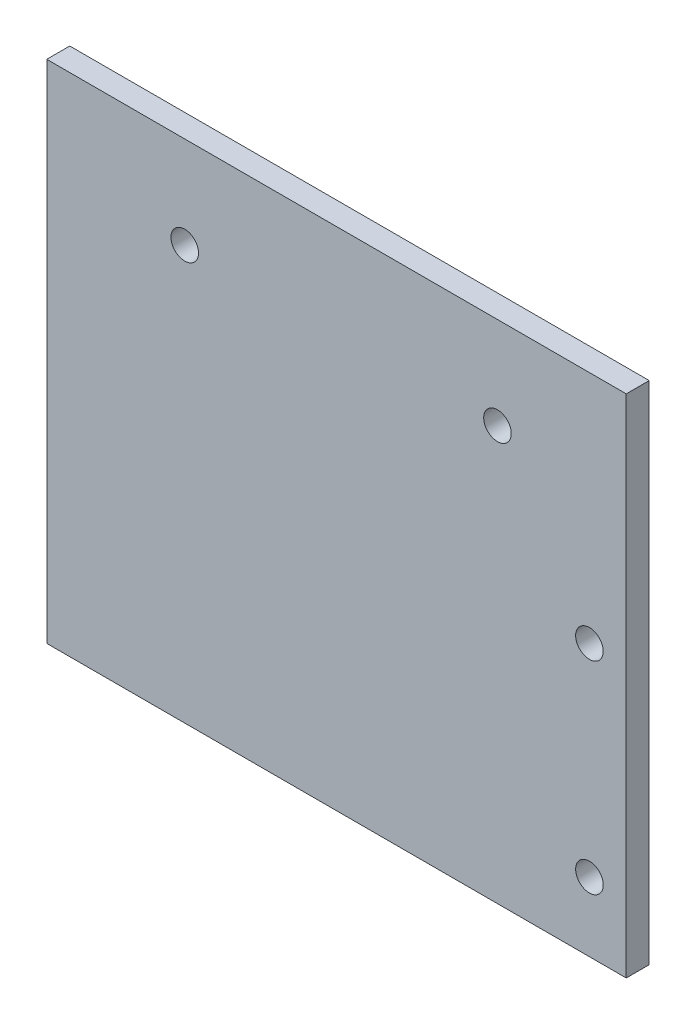
SolidWorks part; units mm, degrees
material "1023 Carbon Steel Sheet (SS)"
ref_plane "Front Plane" through (0, 0, 0) normal (0, 0, 1) x (1, 0, 0)
ref_plane "Top Plane" through (0, 0, 0) normal (0, 1, 0) x (1, 0, 0)
ref_plane "Right Plane" through (0, 0, 0) normal (1, 0, 0) x (0, 0, -1)
sketch "Sketch1" plane through (0, 0, 0) normal (0, 0, 1) x (1, 0, 0)
  line L1 (-81.5, 75) -> (81.5, 75)
  line L2 (-81.5, 75) -> (-81.5, -75)
  line L3 (-81.5, -75) -> (81.5, -75)
  line L4 (81.5, 75) -> (81.5, -75)
  line L5 (-81.5, 75) -> (81.5, -75) construction
  line L6 (-81.5, -75) -> (81.5, 75) construction
  point P0 (0, 0)
  dimension "D1" = 163
  dimension "D2" = 150
extrude "Boss-Extrude1" add sketch "Sketch1" along normal blind 2.5 contours L3 L4 L1 L2
sketch "Sketch3" plane through (0, 0, 2.5) normal (0, 0, 1) x (1, 0, 0)
  line L0 (-81.5, -75) -> (-50.5, -75)
  line L1 (-81.5, 75) -> (-81.5, -75) construction
  line L2 (-81.5, -75) -> (81.5, -75) construction
  line L3 (-50.5, -75) -> (-50.5, -30)
  line L4 (-67.5, -30) -> (-33.5, -30)
  line L5 (-62.5, -56.5) -> (-77.5, -56.5)
  line L6 (-50.5, -30) -> (-62.5, -30)
  line L7 (-50.5, -30) -> (-50.5, -56.5)
  line L8 (-50.5, -56.5) -> (-62.5, -56.5)
  line L9 (-62.5, -30) -> (-62.5, -56.5)
  line L10 (-77.5, -45.5) -> (-77.5, -67.5)
  circle A0 centre (-67.5, -30) radius 1.5
  circle A1 centre (-33.5, -30) radius 1.5
  circle A2 centre (-77.5, -45.5) radius 1.5
  circle A3 centre (-77.5, -67.5) radius 1.5
  point P10 (-50.5, -30)
  point P19 (-77.5, -56.5)
  dimension "D1" = 3
  dimension "D2" = 3
  dimension "D8" = 3
  dimension "D9" = 3
  dimension "D3" = 34
  dimension "D4" = 26.5
  dimension "D5" = 12
  dimension "D6" = 15
  dimension "D7" = 22
  dimension "D10" = 45
  dimension "D11" = 31
extrude "Cut-Extrude1" cut sketch "Sketch3" against normal blind 2.5 contours A1 | A0 | A2 | A3
mirror "Mirror1" about plane through (0, 0, 0) normal (1, 0, 0) of "Cut-Extrude1"
sketch "Sketch4" plane through (0, 0, 2.5) normal (0, 0, 1) x (1, 0, 0)
  line L0 (-81.5, 75) -> (0, 75)
  line L1 (-81.5, 75) -> (81.5, 75) construction
  line L2 (0, 75) -> (0, 10)
  line L3 (0, 10) -> (-32.5, 10)
  line L4 (-32.5, 27.5) -> (-32.5, -7.5)
  line L5 (34.5, -18.5) -> (30.5, -18.5)
  line L6 (-34.5, 38.5) -> (-30.5, 38.5)
  line L7 (-34.5, 38.5) -> (-34.5, 16.5)
  line L8 (-34.5, 16.5) -> (-30.5, 16.5)
  line L9 (-30.5, 38.5) -> (-30.5, 16.5)
  line L10 (-34.5, 38.5) -> (-30.5, 16.5) construction
  line L11 (-34.5, 16.5) -> (-30.5, 38.5) construction
  line L12 (-34.5, 3.5) -> (-30.5, 3.5)
  line L13 (-34.5, 3.5) -> (-34.5, -18.5)
  line L14 (-34.5, -18.5) -> (-30.5, -18.5)
  line L15 (-30.5, 3.5) -> (-30.5, -18.5)
  line L16 (-34.5, 3.5) -> (-30.5, -18.5) construction
  line L17 (-34.5, -18.5) -> (-30.5, 3.5) construction
  line L18 (30.5, 3.5) -> (30.5, -18.5)
  line L19 (34.5, 3.5) -> (30.5, 3.5)
  line L20 (34.5, 3.5) -> (34.5, -18.5)
  line L21 (34.5, 16.5) -> (30.5, 16.5)
  line L22 (30.5, 38.5) -> (30.5, 16.5)
  line L23 (34.5, 38.5) -> (30.5, 38.5)
  line L24 (34.5, 38.5) -> (34.5, 16.5)
  point P11 (-32.5, 10)
  dimension "D1" = 65
  dimension "D2" = 32.5
  dimension "D3" = 22
  dimension "D4" = 22
  dimension "D5" = 4
  dimension "D6" = 4
  dimension "D7" = 35
extrude "Cut-Extrude2" cut sketch "Sketch4" against normal through all contours L21 L22 L23 L24 | L20 L5 L18 L19 | L14 L15 L12 L13 | L9 L8 L7 L6
sketch "Sketch5" plane through (0, 0, 2.5) normal (0, 0, 1) x (1, 0, 0)
  line L0 (-81.5, 75) -> (0, 75)
  line L1 (-81.5, 75) -> (81.5, 75) construction
  line L2 (-81.5, 75) -> (-81.5, -75) construction
  line L3 (0, 75) -> (0, 70)
  line L4 (-28, 70) -> (28, 70)
  circle A0 centre (-28, 70) radius 1.1
  circle A1 centre (28, 70) radius 1.1
  point P11 (0, 70)
  dimension "D3" = 2.2
  dimension "D4" = 2.2
  dimension "D1" = 5
  dimension "D2" = 56
extrude "Cut-Extrude3" cut sketch "Sketch5" against normal through all contours A0 | A1
sketch "Sketch6" plane through (0, 0, 0) normal (0, 0, -1) x (-1, 0, 0)
  line L1 (-81.5, -75) -> (-18.5, -75)
  line L2 (-81.5, -75) -> (-81.5, -20)
  line L3 (-81.5, -20) -> (-18.5, -20)
  line L4 (-18.5, -75) -> (-18.5, -20)
  line L5 (-81.5, -75) -> (81.5, -75)
  line L6 (-81.5, -75) -> (-81.5, 75)
  line L7 (-81.5, 75) -> (81.5, 75)
  line L8 (81.5, -75) -> (81.5, 75)
  circle M3 centre (28, 70) radius 1.1
  circle M4 centre (-28, 70) radius 1.1
  line M5 (-34.5, 16.5) -> (-34.5, 38.5)
  line M6 (-34.5, 38.5) -> (-30.5, 38.5)
  line M7 (-30.5, 38.5) -> (-30.5, 16.5)
  line M8 (-30.5, 16.5) -> (-34.5, 16.5)
  circle M13 centre (33.5, -30) radius 1.5
  circle M14 centre (67.5, -30) radius 1.5
  circle M15 centre (77.5, -45.5) radius 1.5
  circle M16 centre (77.5, -67.5) radius 1.5
  line M17 (81.5, -75) -> (81.5, 75)
  line M18 (81.5, 75) -> (-81.5, 75)
  line M19 (-81.5, 75) -> (-81.5, -75)
  line M20 (-81.5, -75) -> (81.5, -75)
  line M21 (-34.5, -18.5) -> (-34.5, 3.5)
  line M22 (-34.5, 3.5) -> (-30.5, 3.5)
  line M23 (-30.5, 3.5) -> (-30.5, -18.5)
  line M24 (-30.5, -18.5) -> (-34.5, -18.5)
  line M25 (30.5, 3.5) -> (34.5, 3.5)
  line M26 (34.5, 3.5) -> (34.5, -18.5)
  line M27 (34.5, -18.5) -> (30.5, -18.5)
  line M28 (30.5, -18.5) -> (30.5, 3.5)
  line M29 (30.5, 38.5) -> (34.5, 38.5)
  line M30 (34.5, 38.5) -> (34.5, 16.5)
  line M31 (34.5, 16.5) -> (30.5, 16.5)
  line M32 (30.5, 16.5) -> (30.5, 38.5)
  dimension "D1" = 63
  dimension "D2" = 55
extrude "Cut-Extrude4" cut sketch "Sketch6" against normal blind 10 contours L4 L3 M20 M17 M18 M19 M4 M14 M16 M24 M21 M22 M23 M28 M25 M26 M27 M32 M29 M30 M31 M15 M13 M8 M5 M6 M7 M3 | L6 L7 L8 L5
